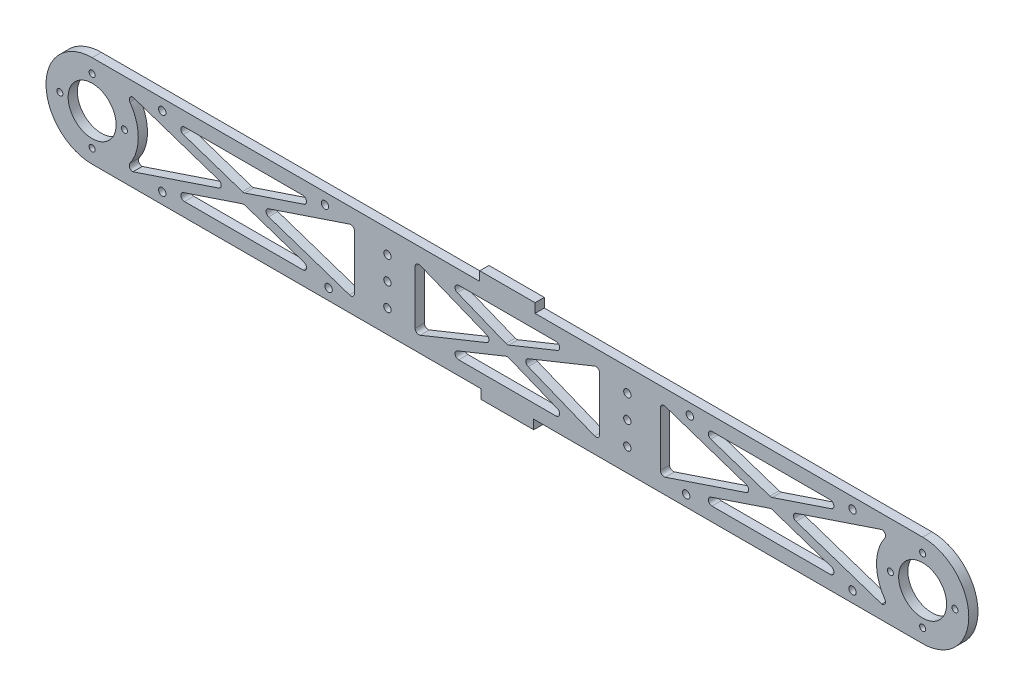
SolidWorks part; units mm, degrees
ref_plane "Front" through (0, 0, 0) normal (0, 0, 1) x (1, 0, 0)
ref_plane "Top" through (0, 0, 0) normal (0, 1, 0) x (1, 0, 0)
ref_plane "Right" through (0, 0, 0) normal (1, 0, 0) x (0, 0, -1)
sketch "草图1" plane through (0, 0, 0) normal (0, 0, 1) x (1, 0, 0)
  line L0 (0, 0) -> (450, 0) construction
  line L1 (0, 25) -> (450, 25)
  line L2 (0, -25) -> (450, -25)
  arc A0 (0, 25) -> (0, -25) centre (0, 0) ccw
  arc A1 (450, -25) -> (450, 25) centre (450, 0) ccw
  circle A2 centre (0, 0) radius 13
  circle A3 centre (17.5, 0) radius 1.65
  circle A4 centre (0, -17.5) radius 1.65
  circle A5 centre (-17.5, 0) radius 1.65
  circle A6 centre (0, 17.5) radius 1.65
  circle A7 centre (450, 0) radius 13
  circle A8 centre (432.5, 0) radius 1.65
  circle A9 centre (450, 17.5) radius 1.65
  circle A10 centre (450, -17.5) radius 1.65
  circle A11 centre (467.5, 0) radius 1.65
  point P3 (225, 0)
  point P21 (0, 0)
  dimension "D1" = 25
  dimension "D3" = 26
  dimension "D4" = 3.3
  dimension "D6" = 4
  dimension "D7" = 26
  dimension "D8" = 3.3
  dimension "D10" = 3.3
  dimension "D11" = 3.3
  dimension "D12" = 3.3
  dimension "D2" = 450
  dimension "D5" = 17.5
  dimension "D9" = 17.5
  dimension "D13" = 17.5
extrude "凸台-拉伸1" add sketch "草图1" along normal blind 5
sketch "草图2" plane through (0, 0, 5) normal (0, 0, 1) x (1, 0, 0)
  line L0 (450, 25) -> (0, 25) construction
  line L1 (0, -25) -> (450, -25) construction
  circle A0 centre (290, 12.5) radius 2
  circle A1 centre (290, 0) radius 2
  circle A2 centre (290, -12.5) radius 2
  circle A4 centre (160, 12.5) radius 2
  circle A6 centre (160, 0) radius 2
  circle A7 centre (160, -12.5) radius 2
  point P23 (160, 12.5)
  point P25 (160, 0)
  point P26 (160, -12.5)
  dimension "D9" = 12.5
  dimension "D7" = 12.5
  dimension "D1" = 4
  dimension "D2" = 4
  dimension "D3" = 4
  dimension "D4" = 12.5
  dimension "D5" = 12.5
  dimension "D6" = 12.5
  dimension "D8" = 12.5
extrude "切除-拉伸2" cut sketch "草图2" against normal blind 5
sketch "草图4" plane through (0, 0, 5) normal (0, 0, 1) x (1, 0, 0)
  line L0 (74.2504, 0) -> (22.1077, -17.5)
  line L1 (82.1077, -2.637) -> (126.3931, -17.5)
  line L2 (37.8223, -17.5) -> (126.3931, -17.5)
  line L3 (37.8223, 17.5) -> (126.3931, 17.5)
  line L4 (142.1077, 17.5) -> (142.1077, -17.5)
  line L5 (89.965, 0) -> (142.1077, -17.5)
  line L6 (82.1077, -2.637) -> (37.8223, -17.5)
  line L7 (22.1077, 17.5) -> (74.2504, 0)
  line L8 (37.8223, 17.5) -> (82.1077, 2.637)
  line L12 (142.1077, 17.5) -> (89.965, 0)
  line L13 (126.3931, 17.5) -> (82.1077, 2.637)
  arc A0 (20.4701, 14.3519) -> (20.4701, -14.3519) centre (0, 0) cw
  arc A4 (22.1077, -17.5) -> (20.4701, -14.3519) centre (22.1077, -15.5) cw
  arc A5 (22.1077, 17.5) -> (20.4701, 14.3519) centre (22.1077, 15.5) ccw
  dimension "D1" = 2
  dimension "D2" = 5
  dimension "D3" = 120
  dimension "D4" = 5
extrude "切除-拉伸3" cut sketch "草图4" against normal blind 5
fillet "圆角1" radius 2 1 edges at (142.1077, 17.5, 2.5)
fillet "圆角2" radius 2 9 edges at (37.8223, -17.5, 2.5) (126.3931, -17.5, 2.5) (37.8223, 17.5, 2.5) (126.3931, 17.5, 2.5) (74.2504, 0, 2.5) (82.1077, -2.637, 2.5) (89.965, 0, 2.5) (82.1077, 2.637, 2.5) (142.1077, -17.5, 2.5)
sketch "草图6" plane through (0, 0, 5) normal (0, 0, 1) x (1, 0, 0)
  line L0 (225, 25) -> (225, -25)
  line L1 (450, 25) -> (0, 25) construction
  line L2 (0, -25) -> (450, -25) construction
sketch "草图7" plane through (0, 25, 0) normal (0, 1, 0) x (1, 0, 0)
  line L0 (225, -5) -> (225, 0)
  line L1 (450, 0) -> (0, 0) construction
ref_plane "基准面1" through (225, 0, 0) normal (1, 0, 0) x (0, 0, -1)
mirror "镜向1" about plane through (225, 0, 0) normal (1, 0, 0) of "切除-拉伸3"
fillet "圆角3" radius 2 10 edges at (323.6069, -17.5, 2.5) (412.1777, -17.5, 2.5) (375.7496, 0, 2.5) (360.035, 0, 2.5) (323.6069, 17.5, 2.5) (412.1777, 17.5, 2.5) (307.8923, -17.5, 2.5) (367.8923, 2.637, 2.5) (367.8923, -2.637, 2.5) (307.8923, 17.5, 2.5)
sketch "草图8" plane through (0, 0, 5) normal (0, 0, 1) x (1, 0, 0)
  line L0 (225, 25) -> (225, -25) construction
  line L1 (198.6417, 17.5) -> (251.3583, 17.5)
  line L2 (175, 14.5352) -> (175, -14.5352)
  line L3 (198.6417, -17.5) -> (251.3583, -17.5)
  line L4 (275, 14.5352) -> (275, -14.5352)
  line L6 (236.2661, -1.8544) -> (272.2509, -16.3896)
  line L7 (450, 25) -> (0, 25) construction
  line L8 (225.7491, 2.9988) -> (252.1073, 13.6456)
  line L9 (236.2661, 1.8544) -> (272.2509, 16.3896)
  line L10 (177.7491, 16.3896) -> (213.7339, 1.8544)
  line L11 (197.8927, 13.6456) -> (224.2509, 2.9988)
  line L12 (225.7491, -2.9988) -> (252.1073, -13.6456)
  line L14 (177.7491, -16.3896) -> (213.7339, -1.8544)
  line L15 (197.8927, -13.6456) -> (224.2509, -2.9988)
  arc A0 (275, -14.5352) -> (272.2509, -16.3896) centre (273, -14.5352) cw
  arc A1 (272.2509, 16.3896) -> (275, 14.5352) centre (273, 14.5352) cw
  arc A2 (236.2661, 1.8544) -> (236.2661, -1.8544) centre (237.0152, 0) ccw
  arc A3 (252.1073, -13.6456) -> (251.3583, -17.5) centre (251.3583, -15.5) cw
  arc A4 (225.7491, -2.9988) -> (224.2509, -2.9988) centre (225, -4.8532) ccw
  arc A5 (198.6417, -17.5) -> (197.8927, -13.6456) centre (198.6417, -15.5) cw
  arc A6 (177.7491, -16.3896) -> (175, -14.5352) centre (177, -14.5352) cw
  arc A7 (213.7339, 1.8544) -> (213.7339, -1.8544) centre (212.9848, 0) cw
  arc A8 (224.2509, 2.9988) -> (225.7491, 2.9988) centre (225, 4.8532) ccw
  arc A9 (251.3583, 17.5) -> (252.1073, 13.6456) centre (251.3583, 15.5) cw
  arc A10 (198.6417, 17.5) -> (197.8927, 13.6456) centre (198.6417, 15.5) ccw
  arc A11 (177.7491, 16.3896) -> (175, 14.5352) centre (177, 14.5352) ccw
  point P0 (225, 0)
  point P21 (275, 17.5)
  point P24 (231.6751, 0)
  point P29 (225, -2.6962)
  point P44 (175, 17.5)
  dimension "D5" = 2
  dimension "D1" = 100
  dimension "D2" = 7.5
  dimension "D3" = 5
  dimension "D4" = 5
extrude "切除-拉伸5" cut sketch "草图8" against normal blind 5
sketch "草图9" plane through (0, 0, 5) normal (0, 0, 1) x (1, 0, 0)
  line L0 (450, 25) -> (0, 25) construction
  line L1 (0, -25) -> (450, -25) construction
  circle A0 centre (38, 19) radius 2
  circle A1 centre (38, -19) radius 2
  circle A2 centre (0, 0) radius 13 construction
  dimension "D1" = 4
  dimension "D2" = 4
  dimension "D3" = 6
  dimension "D4" = 6
  dimension "D5" = 38
  dimension "D6" = 38
extrude "切除-拉伸6" cut sketch "草图9" against normal blind 10
mirror "镜向2" about plane through (225, 0, 0) normal (1, 0, 0) of "切除-拉伸6"
sketch "草图10" plane through (0, 0, 5) normal (0, 0, 1) x (1, 0, 0)
  circle A0 centre (126.1481, 19) radius 2
  circle A1 centre (128.122, -19) radius 2
  arc A2 (114.7845, 13.6039) -> (114.1481, 17.5) centre (114.1481, 15.5) ccw construction
  arc A3 (114.1481, -17.5) -> (114.7845, -13.6039) centre (114.1481, -15.5) ccw construction
  point P11 (116.122, -15.8224)
  dimension "D1" = 4
  dimension "D2" = 4
  dimension "D3" = 12
  dimension "D4" = 12
extrude "切除-拉伸7" cut sketch "草图10" against normal blind 10
mirror "镜向3" about plane through (225, 0, 0) normal (1, 0, 0) of "切除-拉伸7"
sketch "草图11" plane through (0, 25, 0) normal (0, 1, 0) x (1, 0, 0)
  line L0 (240, 0) -> (210, 0)
  line L1 (450, 0) -> (0, 0) construction
  line L2 (240, 0) -> (240, -5)
  line L3 (450, -5) -> (0, -5) construction
  line L4 (240, -5) -> (210, -5)
  line L5 (210, -5) -> (210, 0)
  line L6 (225, -5) -> (225, 0) construction
  dimension "D1" = 15
  dimension "D2" = 15
extrude "凸台-拉伸2" add sketch "草图11" along normal blind 5
sketch "草图12" plane through (0, -25, 0) normal (0, -1, 0) x (1, 0, 0)
  line L0 (225, 5) -> (225, 0) construction
  line L1 (210.7228, 5) -> (239.2772, 5)
  line L2 (210.7228, 5) -> (210.7228, 0)
  line L3 (210.7228, 0) -> (239.2772, 0)
  line L4 (239.2772, 5) -> (239.2772, 0)
  line L5 (210.7228, 5) -> (239.2772, 0) construction
  line L6 (210.7228, 0) -> (239.2772, 5) construction
  line L7 (0, 0) -> (450, 0) construction
  point P0 (225, 2.5)
extrude "凸台-拉伸3" add sketch "草图12" along normal blind 5
